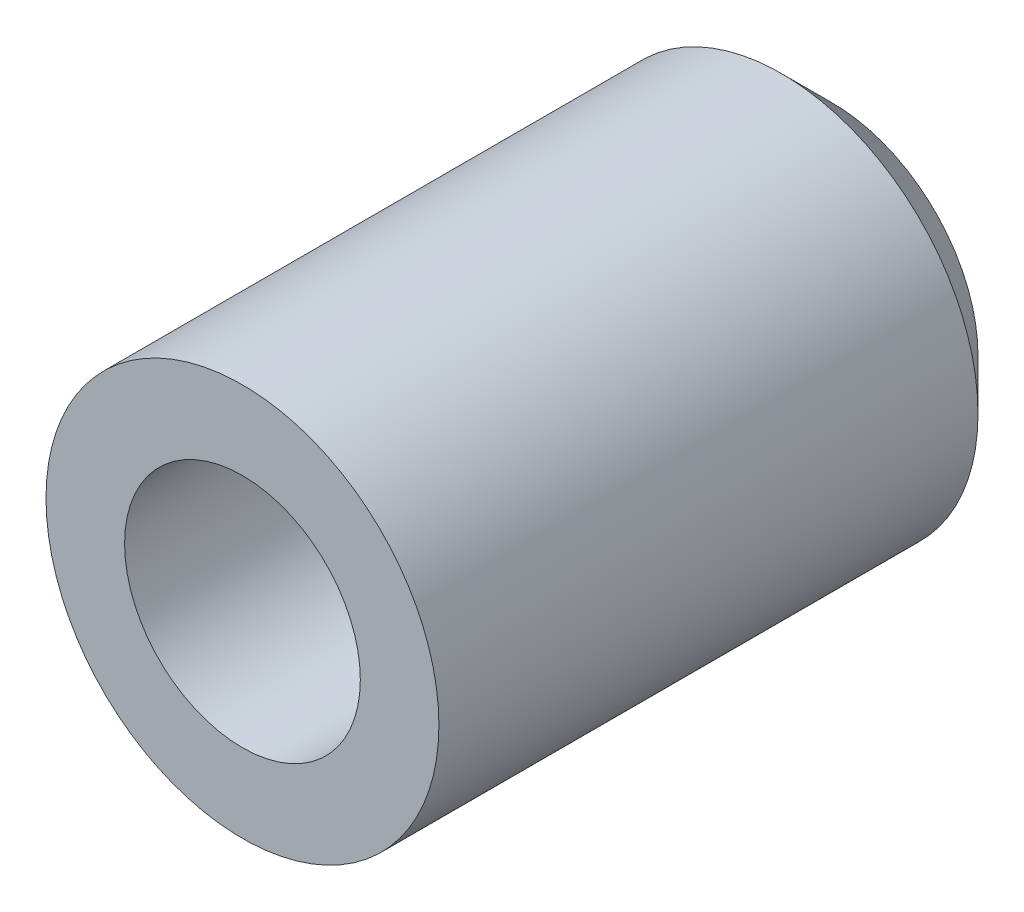
SolidWorks part; units mm, degrees
material "Brass"
ref_plane "Front Plane" through (0, 0, 0) normal (0, 0, 1) x (1, 0, 0)
ref_plane "Top Plane" through (0, 0, 0) normal (0, 1, 0) x (1, 0, 0)
ref_plane "Right Plane" through (0, 0, 0) normal (1, 0, 0) x (0, 0, -1)
sketch "Sketch1" plane through (0, 0, 0) normal (0, 0, 1) x (1, 0, 0)
  circle A0 centre (0, 0) radius 4.7625
  circle A1 centre (0, 0) radius 7.9375
  dimension "D1" = 15.875
  dimension "D2" = 9.525
extrude "Boss-Extrude1" add sketch "Sketch1" along normal mid plane 23.8125
chamfer "Chamfer1" distance 2.032 angle 45 1 edges at (7.9375, 0, -11.9062)
